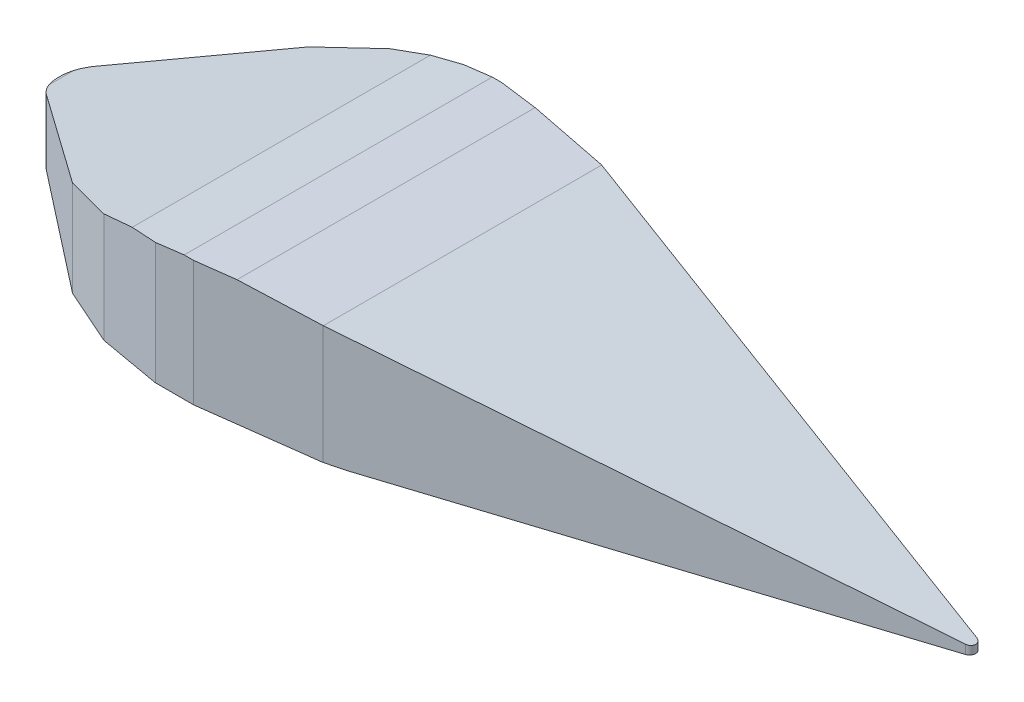
SolidWorks part; units mm, degrees
ref_plane "Front Plane" through (0, 0, 0) normal (0, 0, 1) x (1, 0, 0)
ref_plane "Top Plane" through (0, 0, 0) normal (0, 1, 0) x (1, 0, 0)
ref_plane "Right Plane" through (0, 0, 0) normal (1, 0, 0) x (0, 0, -1)
sketch "Sketch1" plane through (0, 0, 0) normal (0, 1, 0) x (1, 0, 0)
  line L0 (161.4098, 126.0887) -> (784.13, 612.54)
  line L1 (784.13, 612.54) -> (1076.464, 742.696)
  line L2 (1076.464, 742.696) -> (1401.451, 800)
  line L3 (1401.451, 800) -> (1600, 800)
  line L4 (1600, 800) -> (2195.064, 723.196)
  line L5 (2195.064, 723.196) -> (4839.4634, 29.0169)
  line L6 (4839.4634, -29.0169) -> (2195.064, -723.196)
  line L7 (2195.064, -723.196) -> (1600, -800)
  line L8 (1600, -800) -> (1401.451, -800)
  line L9 (1401.451, -800) -> (1076.464, -742.696)
  line L10 (1076.464, -742.696) -> (784.13, -612.54)
  line L11 (784.13, -612.54) -> (161.4098, -126.0887)
  arc A0 (161.4098, 126.0887) -> (161.4098, -126.0887) centre (259.9067, 0) ccw
  arc A1 (4839.4634, 29.0169) -> (4839.4634, -29.0169) centre (4831.8462, 0) cw
  point P15 (0, 0)
  point P18 (4950, 0)
  dimension "r0" = 160
  dimension "r6" = 30
  dimension "x1" = 784.13
  dimension "x2" = 1076.464
  dimension "x3" = 1401.451
  dimension "x4" = 1600
  dimension "x5" = 2195.064
  dimension "x6" = 4950
  dimension "x7" = 2195.064
  dimension "x8" = 1600
  dimension "x9" = 1401.451
  dimension "x10" = 1076.464
  dimension "x11" = 784.13
  dimension "y1" = 612.54
  dimension "y2" = 742.696
  dimension "y3" = 800
  dimension "y5" = 723.196
  dimension "y7" = 723.196
  dimension "y8" = 800
  dimension "y10" = 742.696
  dimension "y11" = 612.54
extrude "TopView_Extrude" add sketch "Sketch1" along normal blind 800
sketch "Sketch2" plane through (0, 0, 0) normal (0, 0, 1) x (1, 0, 0)
  line L0 (0, 300) -> (0, 332.8541)
  line L1 (113.6551, 478.3843) -> (1255.921, 763.655)
  line L2 (1255.921, 763.655) -> (1551.451, 800)
  line L3 (1551.451, 800) -> (1800, 800)
  line L4 (1800, 800) -> (2197.056, 765.81)
  line L5 (2197.056, 765.81) -> (4950, 288.165)
  line L6 (4950, 288.165) -> (4950, 265.638)
  line L7 (4950, 265.638) -> (2301.451, 150)
  line L8 (2301.451, 150) -> (150, 150)
  arc A0 (0, 300) -> (150, 150) centre (150, 300) ccw
  arc A1 (0, 332.8541) -> (113.6551, 478.3843) centre (150, 332.8541) cw
  point P12 (0, 150)
  point P15 (0, 450)
  dimension "r0" = 150
  dimension "r1" = 150
  dimension "x2" = 1255.921
  dimension "x3" = 1551.451
  dimension "x4" = 1800
  dimension "x5" = 2197.056
  dimension "x6" = 4950
  dimension "x8" = 2301.451
  dimension "y0" = 150
  dimension "y1" = 450
  dimension "y2" = 763.655
  dimension "y3" = 800
  dimension "y5" = 765.81
  dimension "y6" = 288.165
  dimension "y7" = 265.638
extrude "SideProfile_Cut" cut sketch "Sketch2" against normal through all and the other way through all flip side to cut
